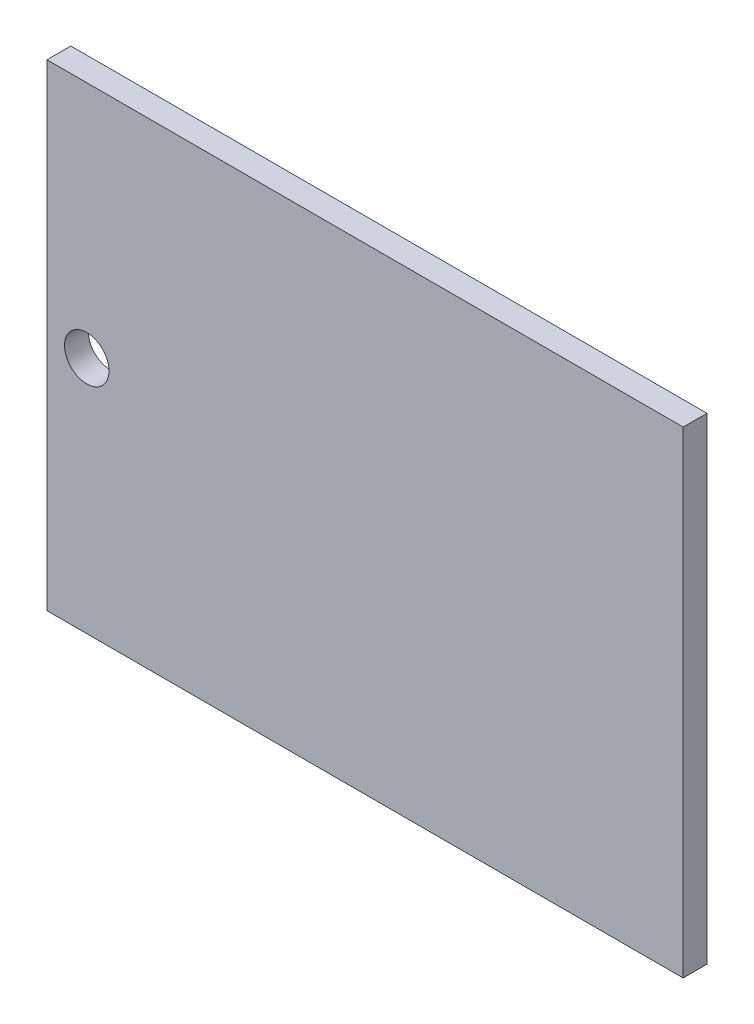
SolidWorks part; units mm, degrees
ref_plane "Front Plane" through (0, 0, 0) normal (0, 0, 1) x (1, 0, 0)
ref_plane "Top Plane" through (0, 0, 0) normal (0, 1, 0) x (1, 0, 0)
ref_plane "Right Plane" through (0, 0, 0) normal (1, 0, 0) x (0, 0, -1)
sketch "Sketch1" plane through (0, 0, 0) normal (0, 0, 1) x (1, 0, 0)
  line L1 (-20, -15) -> (20, -15)
  line L2 (-20, -15) -> (-20, 15)
  line L3 (-20, 15) -> (20, 15)
  line L4 (20, -15) -> (20, 15)
  line L5 (-20, -15) -> (20, 15) construction
  line L6 (-20, 15) -> (20, -15) construction
  point P0 (0, 0)
  dimension "D1" = 40
  dimension "D2" = 30
extrude "Boss-Extrude2" add sketch "Sketch1" along normal blind 1.5
sketch "Sketch2" plane through (0, 0, 1.5) normal (0, 0, 1) x (1, 0, 0)
  line L0 (-20, 15) -> (-20, -15) construction
  line L1 (-20, 0) -> (-17.5, 0) construction
  circle A0 centre (-17.5, 0) radius 1.4
  point P0 (-20, 0)
  dimension "D1" = 15
extrude "Cut-Extrude1" cut sketch "Sketch2" against normal through all
